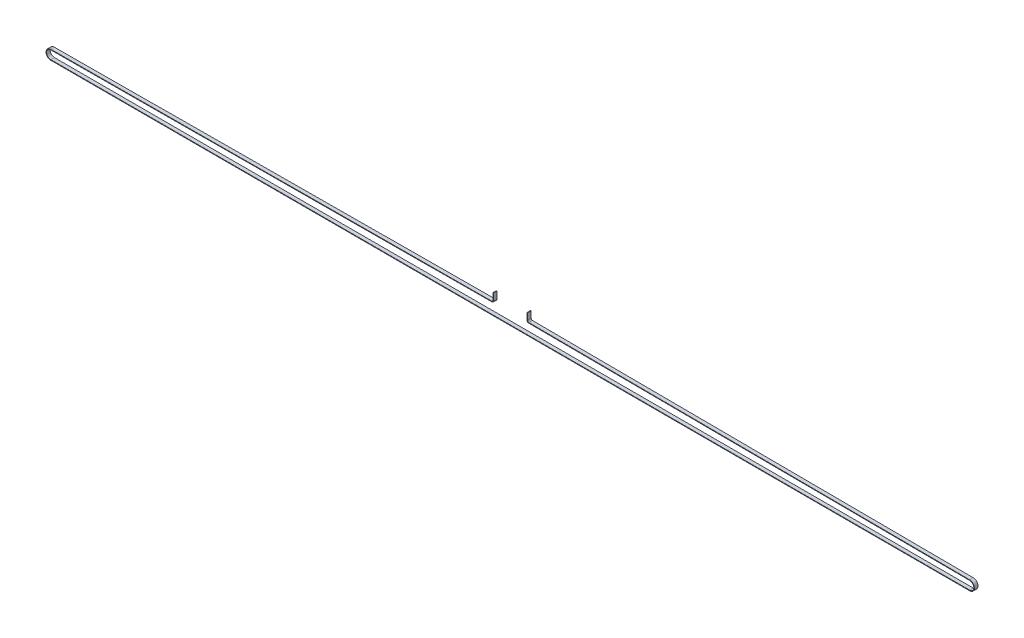
SolidWorks part; units mm, degrees
ref_plane "Front Plane" through (0, 0, 0) normal (0, 0, 1) x (1, 0, 0)
ref_plane "Top Plane" through (0, 0, 0) normal (0, 1, 0) x (1, 0, 0)
ref_plane "Right Plane" through (0, 0, 0) normal (1, 0, 0) x (0, 0, -1)
ref_plane "Plane1" through (0, 0, 0.5636) normal (0, 0, -1) x (-1, 0, 0)
sketch "Sketch1" plane through (0, 0, 0.5636) normal (0, 0, -1) x (-1, 0, 0)
  line L0 (29.2, 33) -> (-29.2, 33)
  line L1 (-29.2, 33) -> (-29.2, 20)
  line L2 (-29.2, 20) -> (-770.0432, 15.9999)
  line L3 (-770, 0) -> (770, 0)
  line L4 (770.0432, 15.9999) -> (29.2, 20)
  line L5 (29.2, 20) -> (29.2, 33)
  arc A0 (-770.0432, 15.9999) -> (-770, 0) centre (-770, 8) ccw
  arc A1 (770, 0) -> (770.0432, 15.9999) centre (770, 8) ccw
  point P10 (0, 33)
  point P11 (0, 0)
  point P12 (0, 0)
  point P14 (0, 0)
  point P15 (0, 0)
  point P16 (0, 0)
  point P17 (0, 0)
  point P18 (-29.2, 20)
  point P19 (0, 0)
  dimension "D2" = 8
  dimension "D5" = 8
  dimension "D1" = 1540
  dimension "D3" = 58.4
  dimension "D4" = 20
  dimension "D6" = 13
extrude "Boss-Extrude1" add sketch "Sketch1" against normal blind 6
sketch "Sketch2" plane through (0, 0, 0.5636) normal (0, 0, -1) x (-1, 0, 0)
  line L12 (28.2, 19.0054) -> (28.2, 32)
  line L13 (28.2, 32) -> (-28.2, 32)
  line L14 (-28.2, 32) -> (-28.2, 19.0054)
  line L15 (-28.2, 19.0054) -> (-770.0378, 14.9999)
  line L16 (-770, 1) -> (770, 1)
  line L17 (770.0378, 14.9999) -> (28.2, 19.0054)
  line L18 (28.2, 19.0054) -> (28.2, 32)
  line L19 (28.2, 32) -> (-28.2, 32)
  line L20 (-28.2, 32) -> (-28.2, 19.0054)
  line L21 (-28.2, 19.0054) -> (-770.0378, 14.9999)
  line L22 (-770, 1) -> (770, 1)
  line L23 (770.0378, 14.9999) -> (28.2, 19.0054)
  arc A4 (-770.0378, 14.9999) -> (-770, 1) centre (-770, 8) ccw
  arc A5 (770, 1) -> (770.0378, 14.9999) centre (770, 8) ccw
  arc A6 (-770.0378, 14.9999) -> (-770, 1) centre (-770, 8) ccw
  arc A7 (770, 1) -> (770.0378, 14.9999) centre (770, 8) ccw
  dimension "D1" = 1
extrude "Cut-Extrude1" cut sketch "Sketch2" against normal through all
sketch "Sketch4" plane through (0, 33, 0) normal (0, 1, 0) x (-1, 0, 0)
  line L4 (-28.2, 0.5636) -> (28.2, 0.5636)
  line L5 (-28.2, 6.5636) -> (-28.2, 0.5636)
  line L6 (28.2, 6.5636) -> (-28.2, 6.5636)
  line L7 (28.2, 0.5636) -> (28.2, 6.5636)
  line L8 (-28.2, 0.5636) -> (28.2, 0.5636)
  line L9 (-28.2, 6.5636) -> (-28.2, 0.5636)
  line L10 (28.2, 6.5636) -> (-28.2, 6.5636)
  line L11 (28.2, 0.5636) -> (28.2, 6.5636)
  dimension "D1" = 0
fillet "Fillet1" radius 2 4 edges at (29.2, 20, 3.5636) (-29.2, 20, 3.5636) (-28.2, 19.0054, 3.5636) (28.2, 19.0054, 3.5636)
extrude "Cut-Extrude4" cut sketch "Sketch4" against normal up to surface (1 mm away) up to face at (0, 32, 3.5636)
